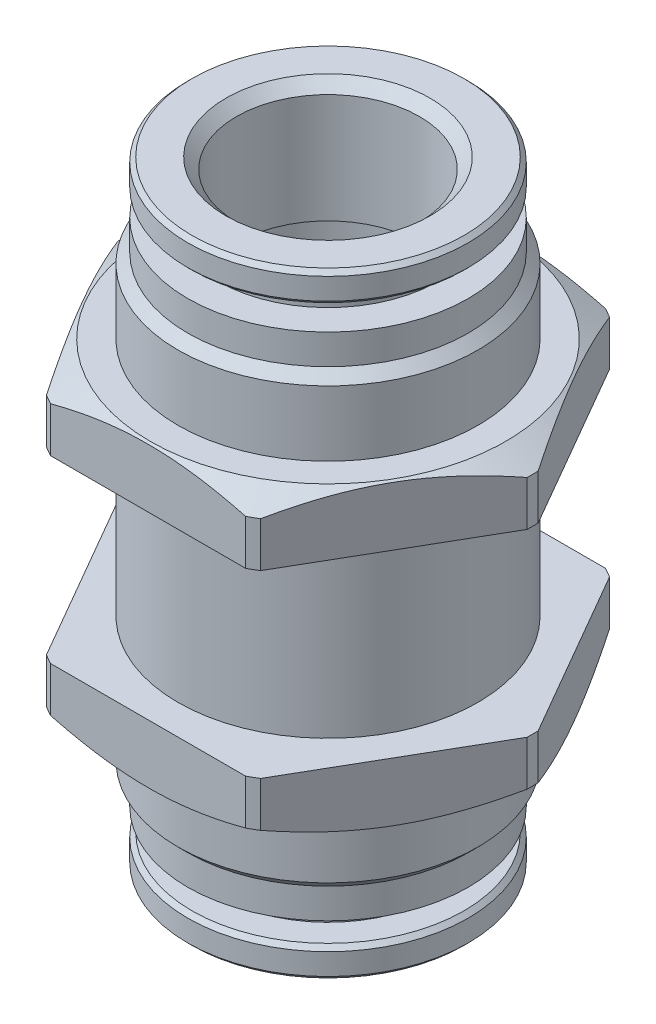
SolidWorks part; units mm, degrees
ref_plane "前基準面" through (0, 0, 0) normal (0, 0, 1) x (1, 0, 0)
ref_plane "上基準面" through (0, 0, 0) normal (0, 1, 0) x (1, 0, 0)
ref_plane "右基準面" through (0, 0, 0) normal (1, 0, 0) x (0, 0, -1)
sketch "草圖1" plane through (0, 0, 0) normal (0, 0, 1) x (1, 0, 0)
  line L0 (0, 26.2488) -> (0, -21.6381) construction
  line L1 (6.1, 12.5) -> (6.1, 19.7929)
  line L2 (6.1, 19.7929) -> (6.8071, 20.5)
  line L3 (6.8071, 20.5) -> (9.0672, 20.5)
  line L4 (9.0672, 20.5) -> (9.35, 20.2172)
  line L5 (9.35, 20.2172) -> (9.35, 18.7828)
  line L6 (9.35, 18.7828) -> (9.0672, 18.5)
  line L7 (9.0672, 18.5) -> (7.35, 18.5)
  line L8 (7.35, 18.5) -> (7.35, 17)
  line L9 (7.35, 17) -> (9.35, 17)
  line L10 (9.35, 17) -> (9.35, 15)
  line L11 (9.35, 15) -> (10, 14.35)
  line L12 (10, 14.35) -> (10, -14.35)
  line L13 (6.1, 12.5) -> (7.1, 12.5)
  line L14 (7.1, 12.5) -> (7.1, 9)
  line L15 (7.1, 9) -> (6.5, 9)
  line L16 (6.2354, 8.3) -> (6.1, 8.3)
  line L17 (6.1, 8.3) -> (6.1, 3.4)
  line L18 (6.1, 3.4) -> (5.75, 3.4)
  line L19 (5.75, 3.4) -> (5.75, -3.4)
  line L20 (0, 0) -> (15.8378, 0) construction
  line L21 (6.1, -3.4) -> (5.75, -3.4)
  line L22 (6.1, -8.3) -> (6.1, -3.4)
  line L23 (6.2354, -8.3) -> (6.1, -8.3)
  line L24 (7.1, -9) -> (6.5, -9)
  line L25 (7.1, -12.5) -> (7.1, -9)
  line L26 (6.1, -12.5) -> (7.1, -12.5)
  line L27 (9.35, -15) -> (10, -14.35)
  line L28 (9.35, -17) -> (9.35, -15)
  line L29 (7.35, -17) -> (9.35, -17)
  line L30 (7.35, -18.5) -> (7.35, -17)
  line L31 (9.0672, -18.5) -> (7.35, -18.5)
  line L32 (9.35, -18.7828) -> (9.0672, -18.5)
  line L33 (9.35, -20.2172) -> (9.35, -18.7828)
  line L34 (9.0672, -20.5) -> (9.35, -20.2172)
  line L35 (6.8071, -20.5) -> (9.0672, -20.5)
  line L36 (6.1, -19.7929) -> (6.8071, -20.5)
  line L37 (6.1, -12.5) -> (6.1, -19.7929)
  line L38 (10, 10) -> (10, 6)
  line L39 (10, 6) -> (13.65, 6)
  line L40 (13.65, 6) -> (13.65, 9)
  line L41 (13.65, 9) -> (11.85, 10)
  line L42 (11.85, 10) -> (10, 10)
  line L43 (13.65, -9) -> (11.85, -10)
  line L44 (13.65, -6) -> (13.65, -9)
  line L45 (10, -6) -> (13.65, -6)
  line L46 (10, -10) -> (10, -6)
  line L47 (11.85, -10) -> (10, -10)
  arc A0 (6.5, 9) -> (6.2354, 8.3) centre (6.5, 8.6) ccw
  arc A1 (6.5, -9) -> (6.2354, -8.3) centre (6.5, -8.6) cw
  point P30 (15.8378, 0)
  point P39 (5.75, 0)
  point P45 (10, 0)
  dimension "D18" = 0.4
  dimension "D1" = 18.7
  dimension "D2" = 2
  dimension "D3" = 1.5
  dimension "D4" = 12.2
  dimension "D5" = 1
  dimension "D6" = 135
  dimension "D7" = 135
  dimension "D8" = 135
  dimension "D9" = 0.4
  dimension "D10" = 2
  dimension "D11" = 2
  dimension "D12" = 135
  dimension "D13" = 20
  dimension "D14" = 41
  dimension "D15" = 8
  dimension "D16" = 11.5
  dimension "D17" = 1
  dimension "D19" = 0.3
  dimension "D20" = 11.5
  dimension "D21" = 17.1
  dimension "D22" = 4
  dimension "D23" = 27.3
  dimension "D24" = 3
  dimension "D25" = 23.7
  dimension "D26" = 6
revolve "旋轉1" add sketch "草圖1" angle 360 about L0
sketch "草圖2" plane through (0, 0, 0) normal (0, 1, 0) x (1, 0, 0)
  line L1 (13.8564, 0) -> (6.9282, 12)
  line L2 (6.9282, 12) -> (-6.9282, 12)
  line L3 (-6.9282, 12) -> (-13.8564, 0)
  line L4 (-13.8564, 0) -> (-6.9282, -12)
  line L5 (-6.9282, -12) -> (6.9282, -12)
  line L6 (6.9282, -12) -> (13.8564, 0)
  circle A0 centre (0, 0) radius 12 construction
  circle A1 centre (0, 0) radius 15.0515
  dimension "D2" = 30.1031
  dimension "D1" = 24
extrude "除料-伸長1" cut sketch "草圖2" against normal through all both and the other way through all
